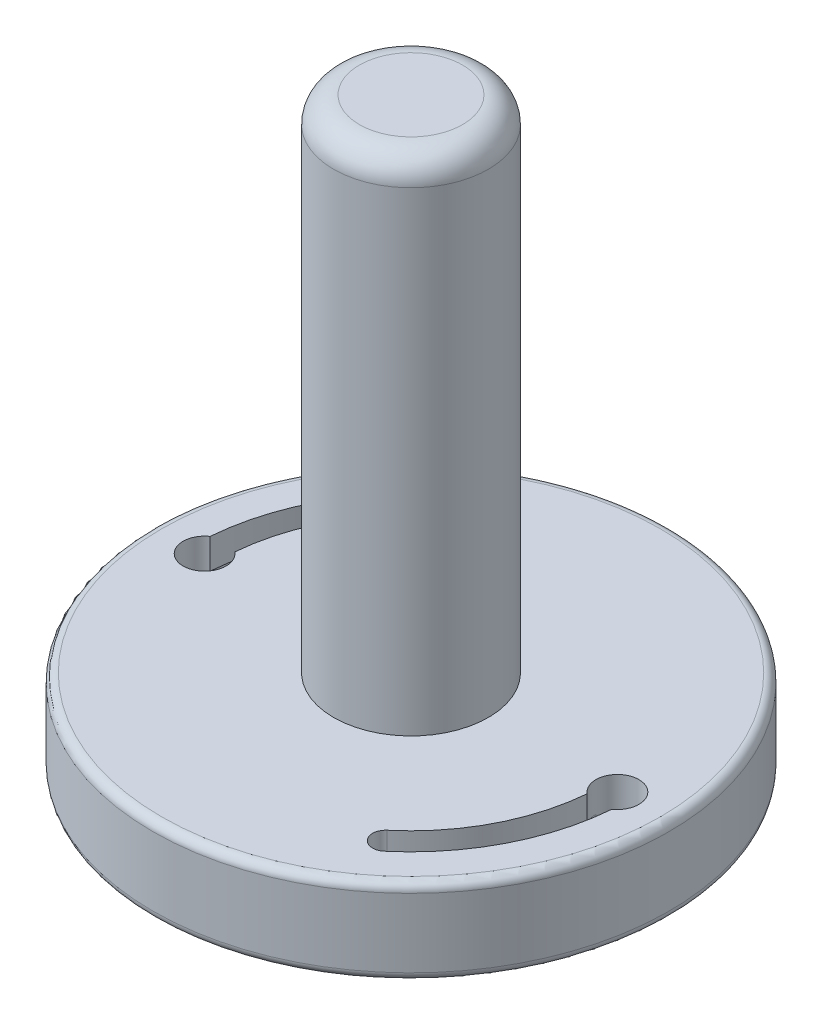
SolidWorks part; units mm, degrees
material "Nylon 101"
ref_plane "Front Plane" through (0, 0, 0) normal (0, 0, 1) x (1, 0, 0)
ref_plane "Top Plane" through (0, 0, 0) normal (0, 1, 0) x (1, 0, 0)
ref_plane "Right Plane" through (0, 0, 0) normal (1, 0, 0) x (0, 0, -1)
sketch "Sketch1" plane through (0, 0, 0) normal (0, 1, 0) x (1, 0, 0)
  circle A0 centre (0, 0) radius 38.1
extrude "Boss-Extrude1" add sketch "Sketch1" along normal blind 12.7
sketch "Sketch2" plane through (0, 12.7, 0) normal (0, 1, 0) x (1, 0, 0)
  circle A0 centre (0, 0) radius 11.43
  dimension "D1" = 22.86
extrude "Boss-Extrude2" add sketch "Sketch2" along normal blind 73.914
sketch "Sketch3" plane through (0, 0, 0) normal (0, -1, 0) x (-1, 0, 0)
  line L0 (0, 0) -> (0, -31.75)
  line L1 (0, 0) -> (-27.4963, 15.875)
  line L2 (0, 0) -> (27.4963, 15.875)
  line L3 (0, 0) -> (3.2996, 1.905)
  line L4 (0, 0) -> (-3.2996, 1.905)
  line L5 (0, 0) -> (0, -3.81)
  line L6 (-3.2996, 1.905) -> (3.2996, 1.905)
  line L7 (-3.2996, 1.905) -> (-3.2996, -31.3982)
  line L8 (3.2996, 1.905) -> (3.2996, -31.3982)
  line L9 (-3.2996, -31.3982) -> (3.2996, -31.3982)
  line L10 (0, -3.81) -> (3.2996, 1.905)
  line L11 (0, -3.81) -> (-29.105, 12.9938)
  line L12 (3.2996, 1.905) -> (-22.5059, 16.8038)
  line L13 (-29.105, 12.9938) -> (-25.8054, 18.7088)
  line L14 (0, -3.81) -> (-3.2996, 1.905)
  line L15 (0, -3.81) -> (28.9716, 12.9168)
  line L16 (-3.2996, 1.905) -> (8.9711, 8.9894)
  line L17 (28.9716, 12.9168) -> (25.672, 18.6318)
  line L18 (25.672, 18.6318) -> (23.2759, 21.5939)
  line L20 (-25.8054, 18.7088) -> (-23.2759, 21.5939)
  line L21 (-25.8054, 18.7088) -> (-25.6976, 18.6465)
  line L22 (-25.6976, 18.6465) -> (-25.8054, 18.7088)
  line L24 (-8.9711, 8.9894) -> (-12.2706, 10.8944)
  line L25 (-9.8562, 9.5005) -> (-13.1557, 11.4055)
  line L26 (-8.9711, 8.9894) -> (-5.901, 11.2458)
  line L27 (5.901, 11.2458) -> (5.8917, 11.2507)
  line L28 (12.2706, 10.8944) -> (22.3725, 16.7268)
  arc A0 (5.9327, 11.2291) -> (8.9711, 8.9894) centre (0, 0) ccw
  circle A1 centre (0, 0) radius 31.75
  arc A2 (22.3725, 16.7268) -> (23.2759, 21.5939) centre (19.9763, 19.6889) ccw
  arc A3 (-23.2759, 21.5939) -> (-22.5059, 16.8038) centre (-19.9902, 19.6651) ccw
  arc A4 (5.901, 11.2458) -> (12.2706, 10.8944) centre (9.467, 17.9799) ccw
  circle A5 centre (-9.467, 17.9799) radius 7.62
  dimension "D1" = 25.4
  dimension "D10" = 7.62
  dimension "D12" = 7.62
  dimension "D18" = 15.24
  dimension "D19" = 3.81
  dimension "D2" = 31.75
  dimension "D3" = 120
  dimension "D4" = 120
  dimension "D5" = 3.81
  dimension "D6" = 3.81
  dimension "D7" = 3.81
  dimension "D8" = 3.81
  dimension "D9" = 3.81
  dimension "D11" = 3.81
  dimension "D13" = 29.6435
  dimension "D14" = 3.81
  dimension "D15" = 3.81
  dimension "D16" = 29.7975
  dimension "D17" = 3.81
fillet "Fillet1" radius 1.27 1 edges at (0, 12.7, 38.1)
fillet "Fillet2" radius 1.27 1 edges at (0, 0, 38.1)
fillet "Fillet3" radius 3.81 1 edges at (0, 86.614, 11.43)
ref_plane "Plane1" through (0, 5.08, 0) normal (0, -1, 0) x (-1, 0, 0)
sketch "Sketch4" plane through (0, 12.7, 0) normal (0, 1, 0) x (1, 0, 0)
  line L0 (0, 0) -> (-30.48, 0) construction
  line L1 (0, 0) -> (-19.5922, 23.349) construction
  arc A0 (-32.2792, 2.616) -> (-28.4692, 2.4571) centre (-30.48, 0) ccw
  arc A1 (32.2792, -2.616) -> (28.4692, -2.4571) centre (30.48, 0) ccw
  arc A2 (-18.3677, 21.8897) -> (-28.4692, 2.4571) centre (0, 0) ccw
  arc A3 (-20.8167, 24.8083) -> (-32.2792, 2.616) centre (0, 0) ccw
  arc A4 (-18.3677, 21.8897) -> (-20.8167, 24.8083) centre (-19.5922, 23.349) ccw
  arc A5 (18.3677, -21.8897) -> (28.4692, -2.4571) centre (0, 0) ccw
  arc A6 (20.8167, -24.8083) -> (32.2792, -2.616) centre (0, 0) ccw
  arc A7 (18.3677, -21.8897) -> (20.8167, -24.8083) centre (19.5922, -23.349) ccw
  point P3 (0, 0)
  point P17 (0, 0)
  dimension "D1" = 30.48
  dimension "D2" = 3.81
  dimension "D3" = 3.175
  dimension "D4" = 1.905
  dimension "D7" = 28.575
  dimension "D5" = 50
  dimension "D6" = 2
extrude "Cut-Extrude1" cut sketch "Sketch4" against normal blind 4.445
sketch "Sketch5" plane through (0, 8.255, 0) normal (0, 1, 0) x (1, 0, 0)
  arc A0 (-21.633, 25.7812) -> (-33.655, 0) centre (0, 0) ccw
  arc A1 (-33.655, 0) -> (-27.305, 0) centre (-30.48, 0) ccw
  arc A2 (-17.5513, 20.9168) -> (-21.633, 25.7812) centre (-19.5922, 23.349) ccw
  arc A3 (-17.5513, 20.9168) -> (-27.305, 0) centre (0, 0) ccw
  arc A4 (33.655, 0) -> (27.305, 0) centre (30.48, 0) ccw
  arc A5 (17.5513, -20.9168) -> (27.305, 0) centre (0, 0) ccw
  arc A6 (21.633, -25.7812) -> (33.655, 0) centre (0, 0) ccw
  arc A7 (17.5513, -20.9168) -> (21.633, -25.7812) centre (19.5922, -23.349) ccw
  point P9 (-33.655, 0)
  point P11 (-33.655, 0)
  point P21 (0, 0)
  dimension "D1" = 6.35
  dimension "D2" = 6.35
  dimension "D3" = 2
extrude "Cut-Extrude2" cut sketch "Sketch5" against normal blind 3.175
